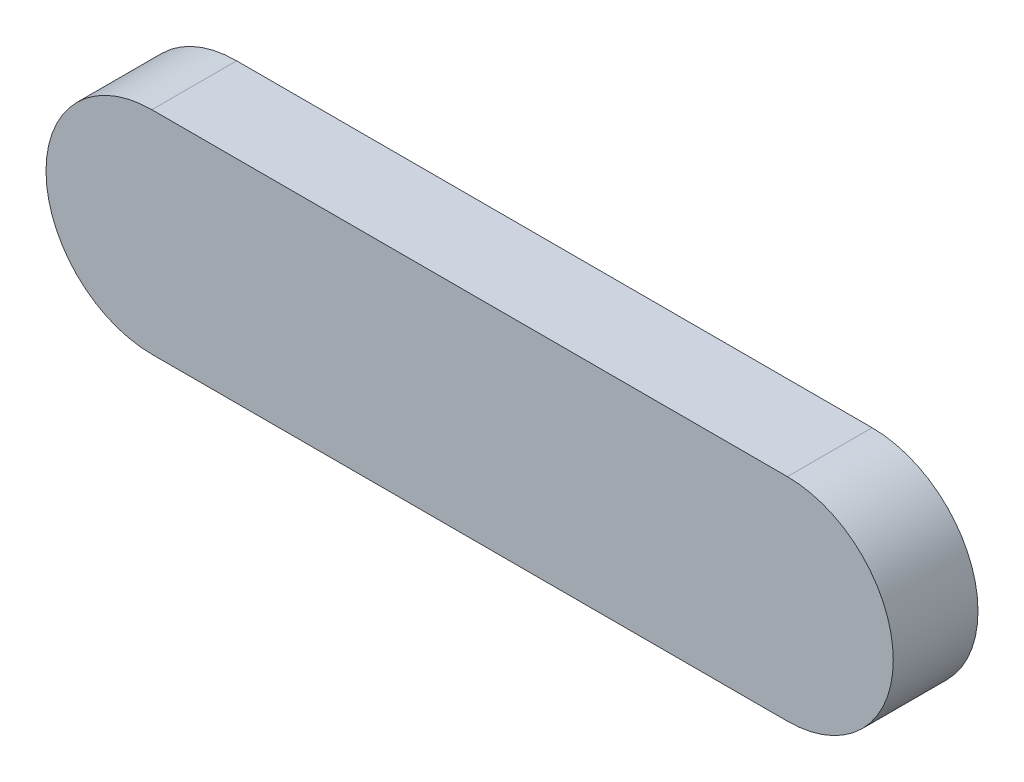
SolidWorks part; units mm, degrees
ref_plane "前视基准面" through (0, 0, 0) normal (0, 0, 1) x (1, 0, 0)
ref_plane "上视基准面" through (0, 0, 0) normal (0, 1, 0) x (1, 0, 0)
ref_plane "右视基准面" through (0, 0, 0) normal (1, 0, 0) x (0, 0, -1)
sketch "草图1" plane through (0, 0, 0) normal (0, 0, 1) x (1, 0, 0)
  line L0 (0, 0) -> (150, 0) construction
  line L1 (0, 25) -> (150, 25)
  line L2 (0, -25) -> (150, -25)
  arc A0 (0, 25) -> (0, -25) centre (0, 0) ccw
  arc A1 (150, -25) -> (150, 25) centre (150, 0) ccw
  point P3 (75, 0)
  dimension "D2" = 25
  dimension "D1" = 150
extrude "凸台-拉伸1" add sketch "草图1" along normal blind 20
